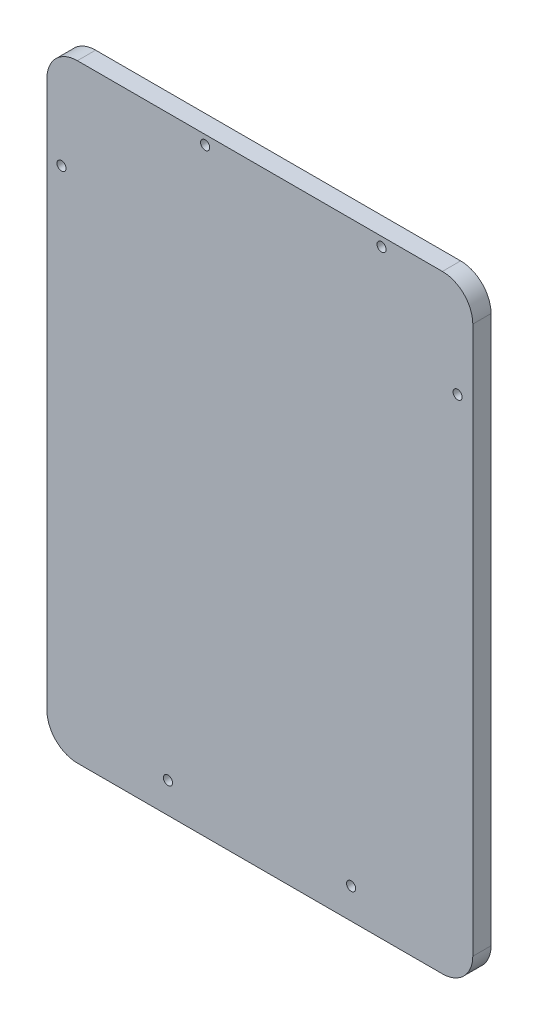
SolidWorks part; units mm, degrees
ref_plane "Front Plane" through (0, 0, 0) normal (0, 0, 1) x (1, 0, 0)
ref_plane "Top Plane" through (0, 0, 0) normal (0, 1, 0) x (1, 0, 0)
ref_plane "Right Plane" through (0, 0, 0) normal (1, 0, 0) x (0, 0, -1)
sketch "Sketch1" plane through (0, 0, 0) normal (0, 0, 1) x (1, 0, 0)
  line L1 (0, 0) -> (140, 0)
  line L2 (0, 0) -> (0, 200)
  line L3 (0, 200) -> (140, 200)
  line L4 (140, 0) -> (140, 200)
  dimension "D1" = 200
  dimension "D2" = 140
extrude "Boss-Extrude1" add sketch "Sketch1" along normal blind 6
fillet "Fillet1" radius 10 4 edges at (0, 0, 3) (140, 0, 3) (0, 200, 3) (140, 200, 3)
sketch "Sketch2" plane through (0, 0, 0) normal (0, 0, -1) x (-1, 0, 0)
  line L0 (-10, 0) -> (-130, 0) construction
  line L1 (-140, 10) -> (-140, 190) construction
  circle A0 centre (-100, 10) radius 1.5
  circle A1 centre (-39.78, 10) radius 1.5
  circle A2 centre (-135, 167.45) radius 1.5
  circle A3 centre (-4.78, 167.45) radius 1.5
  point P11 (0, 0)
  dimension "D1" = 3
  dimension "D2" = 3
  dimension "D6" = 3
  dimension "D7" = 3
  dimension "D8" = 35
  dimension "D3" = 10
  dimension "D4" = 60.22
  dimension "D5" = 40
  dimension "D9" = 157.45
  dimension "D10" = 35
extrude "Cut-Extrude1" cut sketch "Sketch2" against normal blind 10
sketch "Sketch3" plane through (0, 0, 0) normal (0, 0, -1) x (-1, 0, 0)
  line L3 (-140, 10) -> (-140, 190) construction
  circle A0 centre (-110, 196.9903) radius 1.5
  circle A1 centre (-52, 196.9903) radius 1.5
  point P4 (0, 0)
  dimension "D1" = 3
  dimension "D2" = 3
  dimension "D3" = 58
  dimension "D4" = 30
extrude "Cut-Extrude2" cut sketch "Sketch3" against normal blind 10
